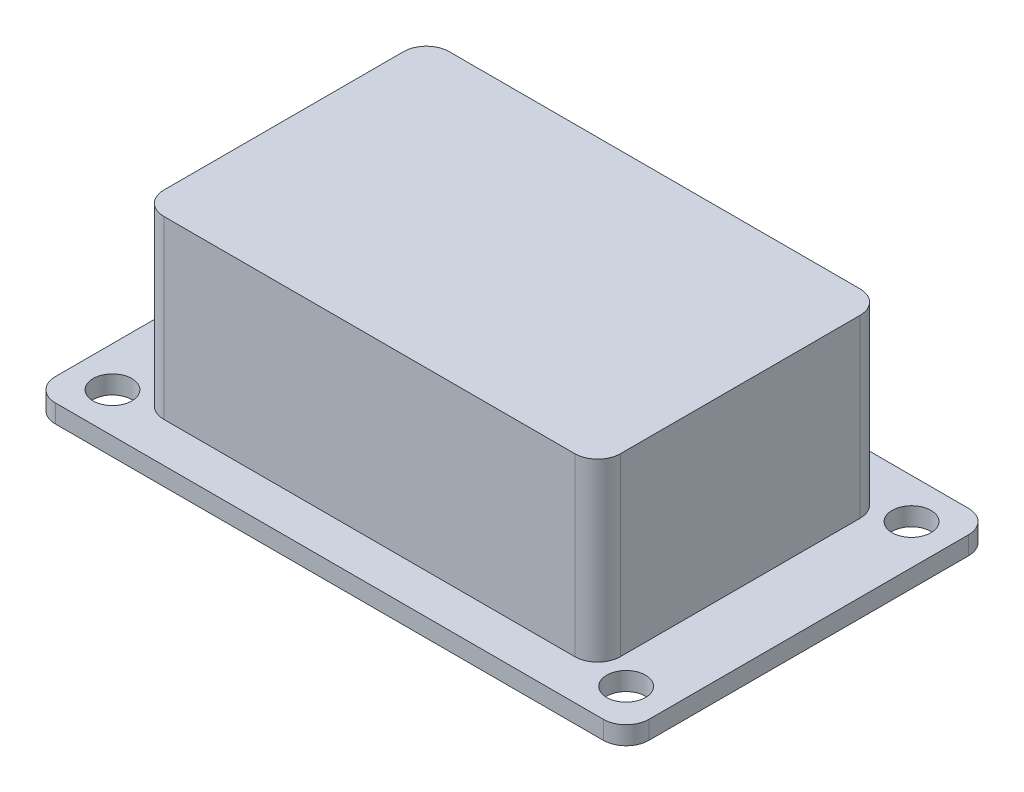
SolidWorks part; units mm, degrees
ref_plane "Front Plane" through (0, 0, 0) normal (0, 0, 1) x (1, 0, 0)
ref_plane "Top Plane" through (0, 0, 0) normal (0, 1, 0) x (1, 0, 0)
ref_plane "Right Plane" through (0, 0, 0) normal (1, 0, 0) x (0, 0, -1)
sketch "Sketch1" plane through (0, 0, 0) normal (0, 1, 0) x (1, 0, 0)
  line L0 (-24, -16) -> (24, -16)
  line L1 (26, -14) -> (26, 14)
  line L2 (24, 16) -> (-24, 16)
  line L3 (-26, 14) -> (-26, -14)
  arc A0 (24, -16) -> (26, -14) centre (24, -14) ccw
  arc A1 (26, 14) -> (24, 16) centre (24, 14) ccw
  arc A2 (-24, 16) -> (-26, 14) centre (-24, 14) ccw
  arc A3 (-26, -14) -> (-24, -16) centre (-24, -14) ccw
extrude "Boss-Extrude1" add sketch "Sketch1" along normal blind 1.6
ref_plane "Plane1" through (0, 1.6, 0) normal (0, 1, 0) x (1, 0, 0)
sketch "Sketch2" plane through (0, 1.6, 0) normal (0, 1, 0) x (1, 0, 0)
  line L0 (-18, -12.5) -> (18, -12.5)
  line L1 (20, -10.5) -> (20, 10.5)
  line L2 (18, 12.5) -> (-18, 12.5)
  line L3 (-20, 10.5) -> (-20, -10.5)
  arc A0 (18, -12.5) -> (20, -10.5) centre (18, -10.5) ccw
  arc A1 (20, 10.5) -> (18, 12.5) centre (18, 10.5) ccw
  arc A2 (-18, 12.5) -> (-20, 10.5) centre (-18, 10.5) ccw
  arc A3 (-20, -10.5) -> (-18, -12.5) centre (-18, -10.5) ccw
extrude "Boss-Extrude2" add sketch "Sketch2" along normal blind 15.4
sketch "Sketch3" plane through (0, 0, 0) normal (0, 1, 0) x (1, 0, 0)
  circle A0 centre (22.5, -12.5) radius 1.7
  circle A1 centre (22.5, 12.5) radius 1.7
  circle A2 centre (-22.5, -12.5) radius 1.7
  circle A3 centre (-22.5, 12.5) radius 1.7
extrude "Cut-Extrude1" cut sketch "Sketch3" along normal blind 1.6
